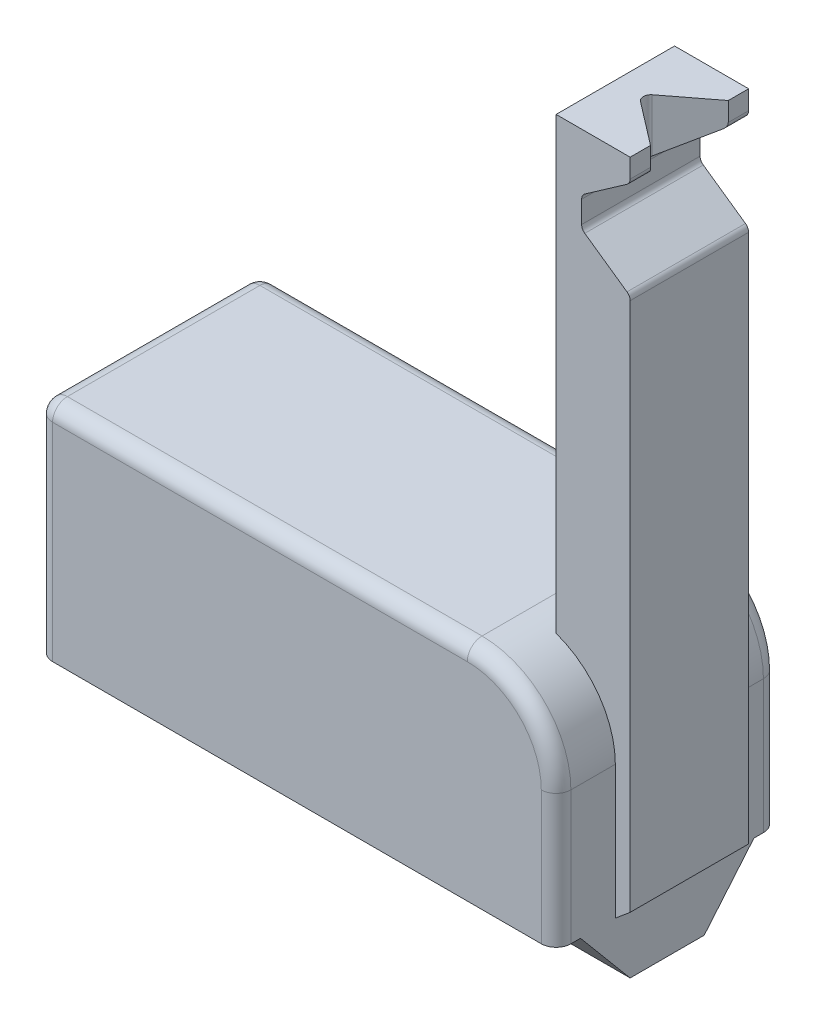
SolidWorks part; units mm, degrees
ref_plane "Plan de face" through (0, 0, 0) normal (0, 0, 1) x (1, 0, 0)
ref_plane "Plan de dessus" through (0, 0, 0) normal (0, 1, 0) x (1, 0, 0)
ref_plane "Plan de droite" through (0, 0, 0) normal (1, 0, 0) x (0, 0, -1)
sketch "Esquisse1" plane through (0, 0, 0) normal (0, 0, 1) x (1, 0, 0)
  line L1 (0, 0) -> (35, 0)
  line L2 (0, 0) -> (0, 15)
  line L3 (0, 15) -> (29, 15)
  line L4 (35, 0) -> (35, 9)
  arc A0 (35, 9) -> (29, 15) centre (29, 9) ccw
  point P7 (35, 15)
  dimension "D3" = 6
  dimension "D1" = 35
  dimension "D2" = 15
extrude "Boss.-Extru.1" add sketch "Esquisse1" along normal blind 15
sketch "Esquisse2" plane through (0, 0, 0) normal (0, -1, 0) x (1, 0, 0)
  line L0 (35, 15) -> (35, 0) construction
  line L1 (31, 11) -> (36, 11)
  line L2 (31, 11) -> (31, 3)
  line L3 (31, 3) -> (36, 3)
  line L4 (36, 11) -> (36, 3)
  line L5 (0, 0) -> (35, 0) construction
  dimension "D1" = 8
  dimension "D2" = 5
  dimension "D3" = 1
  dimension "D4" = 3
extrude "Boss.-Extru.2" add sketch "Esquisse2" against normal blind 45
sketch "Esquisse3" plane through (0, 0, 3) normal (0, 0, -1) x (-1, 0, 0)
  line L0 (-36, 43.4558) -> (-36, 36.8672)
  line L1 (-36, 45) -> (-36, 0) construction
  line L3 (-32.7234, 41.1615) -> (-32.7234, 39.1615)
  line L4 (-36, 43.4558) -> (-32.7234, 41.1615)
  line L5 (-36, 36.8672) -> (-32.7234, 39.1615)
  dimension "D1" = 70
  dimension "D2" = 2
  dimension "D3" = 4
  dimension "D4" = 4
extrude "Enlèv. mat.-Extru.1" cut sketch "Esquisse3" against normal through all
fillet "Congé1" radius 0.5 4 edges at (36, 36.8672, 7) (36, 43.4558, 7) (32.7234, 39.1615, 7) (32.7234, 41.1615, 7)
sketch "Esquisse4" plane through (0, 45, 0) normal (0, 1, 0) x (1, 0, 0)
  line L0 (36, -4.3747) -> (33.0956, -6.6033)
  line L1 (36, -3) -> (36, -11) construction
  line L2 (36, -7) -> (36.4966, -7) construction
  line L3 (36, -9.6253) -> (33.0956, -7.3967)
  line L4 (36, -4.3747) -> (36, -9.6253)
  arc A0 (33.0956, -6.6033) -> (33.0956, -7.3967) centre (33.4, -7) ccw
  point P9 (32.5787, -7)
  dimension "D1" = 0.5
  dimension "D2" = 2.6
  dimension "D3" = 75
extrude "Enlèv. mat.-Extru.2" cut sketch "Esquisse4" against normal blind 5
sketch "Esquisse6" plane through (0, 0, 0) normal (-1, 0, 0) x (0, 0, 1)
  line L0 (13.3564, 0) -> (1.6436, 0)
  line L1 (15, 0) -> (0, 0) construction
  line L2 (5, -4) -> (10, -4)
  line L3 (10, -4) -> (13.3564, 0)
  line L4 (5, -4) -> (1.6436, 0)
  dimension "D3" = 130
extrude "Boss.-Extru.4" add sketch "Esquisse6" against normal up to surface (35 mm away) up to face at (35, 4.5, 13)
fillet "Congé3" radius 1 9 edges at (35, 4.5, 0) (33.2426, 13.2426, 0) (14.5, 15, 0) (35, 4.5, 15) (33.2426, 13.2426, 15) (14.5, 15, 15) (0, 15, 7.5) (0, 7.5, 15) (0, 7.5, 0)
draft "Dépouille2" type of draft neutral plane draft angle 40 faces to draft 1 face at (35.5, 0, 6) neutral plane through (35, 0, 15) neutral plane normal (1, 0, 0) parameters "D1"=40
